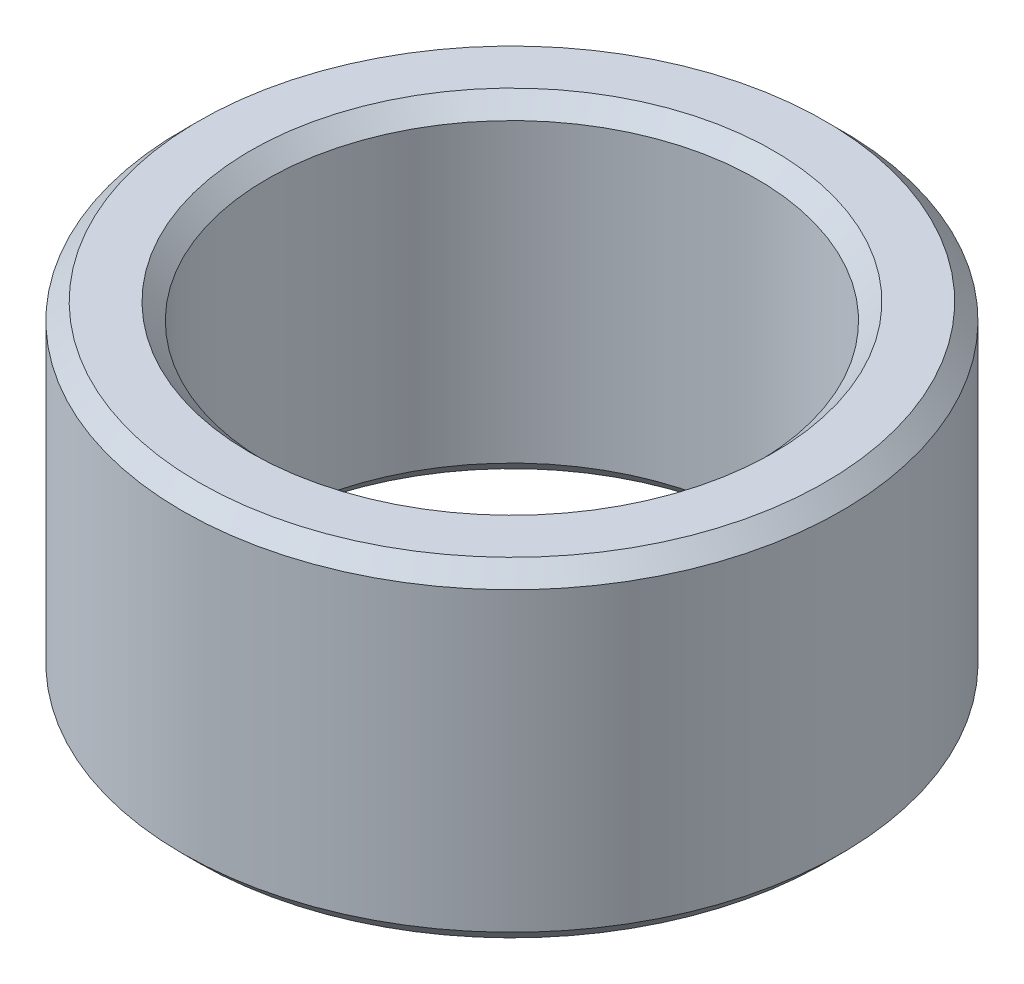
SolidWorks part; units mm, degrees
material "黄铜"
ref_plane "前视基准面" through (0, 0, 0) normal (0, 0, 1) x (1, 0, 0)
ref_plane "上视基准面" through (0, 0, 0) normal (0, 1, 0) x (1, 0, 0)
ref_plane "右视基准面" through (0, 0, 0) normal (1, 0, 0) x (0, 0, -1)
other "Configuration Table"
sketch "草图1" plane through (0, 0, 0) normal (0, 1, 0) x (1, 0, 0)
  circle A0 centre (0, 0) radius 4
  circle A1 centre (0, 0) radius 2.975
  dimension "D1" = 5.95
  dimension "D2" = 8
extrude "凸台-拉伸1" add sketch "草图1" along normal blind 4
chamfer "倒角1" distance 0.2 angle 45 4 edges at (0, 0, 2.975) (0, 0, 4) (0, 4, 4) (0, 4, 2.975)
